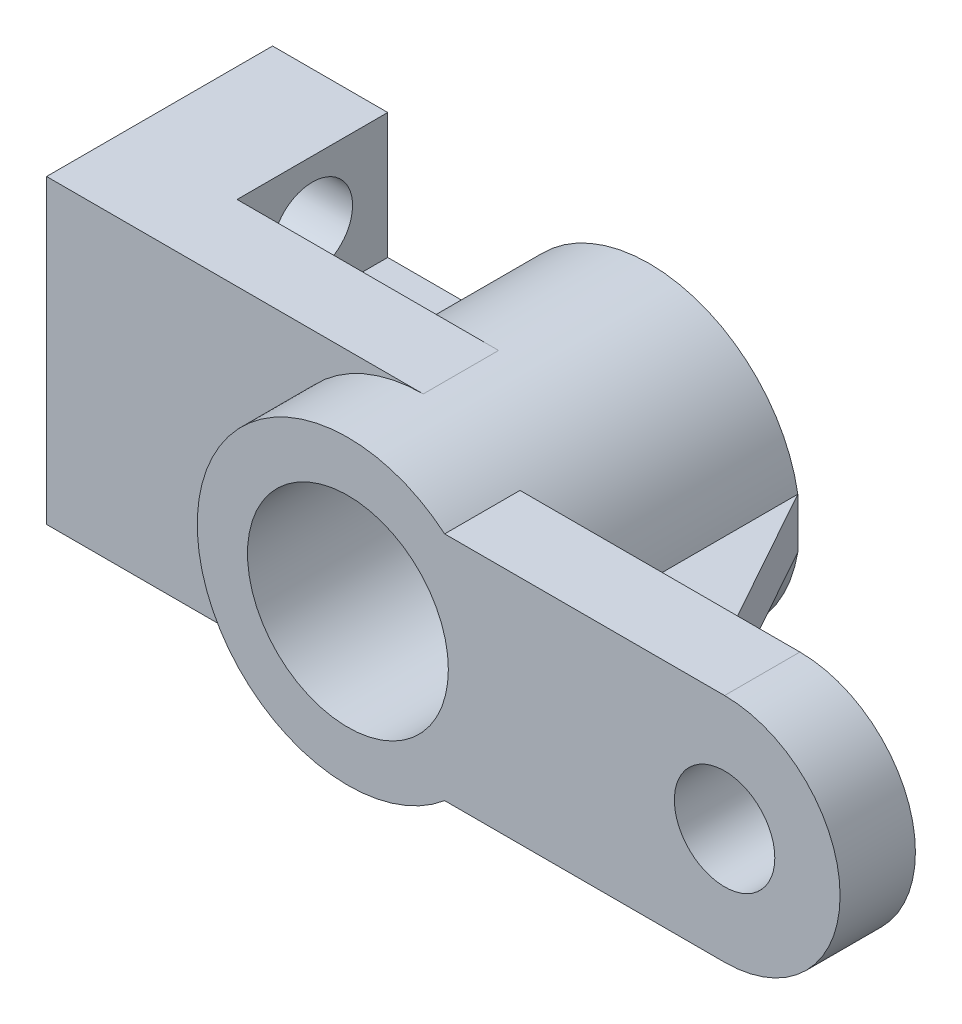
SolidWorks part; units mm, degrees
ref_plane "Front Plane" through (0, 0, 0) normal (0, 0, 1) x (1, 0, 0)
ref_plane "Top Plane" through (0, 0, 0) normal (0, 1, 0) x (1, 0, 0)
ref_plane "Right Plane" through (0, 0, 0) normal (1, 0, 0) x (0, 0, -1)
sketch "Sketch1" plane through (0, 0, 0) normal (0, 0, 1) x (1, 0, 0)
  circle A0 centre (0, 0) radius 30
  circle A1 centre (0, 0) radius 20
  dimension "D1" = 60
  dimension "D2" = 40
extrude "Boss-Extrude1" add sketch "Sketch1" along normal blind 60
sketch "Sketch2" plane through (0, 0, 60) normal (0, 0, 1) x (1, 0, 0)
  line L0 (19.2614, 23) -> (75, 23)
  line L1 (75, -23) -> (19.2614, -23)
  line L2 (0, 0) -> (75, 0) construction
  circle A0 centre (0, 0) radius 30 construction
  arc A1 (75, 23) -> (75, -23) centre (75, 0) cw
  circle A2 centre (75, 0) radius 10
  dimension "D1" = 23
  dimension "D2" = 20
  dimension "D3" = 75
extrude "Boss-Extrude3" add sketch "Sketch2" against normal blind 15
sketch "Sketch3" plane through (0, 0, 60) normal (0, 0, 1) x (1, 0, 0)
  line L0 (0, -30) -> (-75, -30)
  line L1 (0, 30) -> (-75, 30)
  line L2 (-75, 30) -> (-75, -30)
  arc A0 (19.2614, 23) -> (19.2614, -23) centre (0, 0) ccw construction
  arc A1 (0, 30) -> (0, -30) centre (0, 0) ccw
  dimension "D1" = 75
  dimension "D2" = 60
extrude "Boss-Extrude4" add sketch "Sketch3" against normal blind 15 from offset 15 offset against normal yes
sketch "Sketch5" plane through (0, 0, 0) normal (0, 0, -1) x (-1, 0, 0)
  line L0 (30, 0) -> (75, 0) construction
  line L2 (75, 30) -> (52.0709, 30)
  line L3 (0, 30) -> (75, 30) construction
  line L4 (52.0709, 30) -> (52.0709, 5)
  line L5 (75, -30) -> (0, -30) construction
  line L6 (52.0709, -30) -> (75, -30)
  line L7 (75, -5) -> (75, -4.9263)
  line L8 (52.0709, 5) -> (29.5804, 5)
  line L9 (75.2145, -5) -> (75, -5)
  line L11 (75.2145, 5) -> (75, 5)
  line L13 (75.2145, -5) -> (75, -4.9263) construction
  line L14 (75.2145, 5) -> (75, 4.981) construction
  line L17 (52.0709, -5) -> (29.5804, -5)
  line L18 (75, 4.981) -> (75, 5)
  line L19 (75, -30) -> (75, 30)
  line L20 (52.0709, -5) -> (52.0709, -30)
  arc A1 (0, -30) -> (0, 30) centre (0, 0) ccw construction
  arc A2 (29.5804, -5) -> (29.5804, 5) centre (0, 0) ccw
  point P11 (52.0709, 2.9503)
  circle M6 centre (0, 0) radius 30
  dimension "D1" = 5
extrude "Boss-Extrude8" add sketch "Sketch5" against normal up to surface (30 mm away) contours L17 L20 L6 L19 L7 L18 L2 L4 L8 M6 up to face at (-45, 0, 30)
sketch "Sketch9" plane through (-75, 0, 0) normal (-1, 0, 0) x (0, 0, 1)
  line L0 (0, 0) -> (45, 0) construction
  line L1 (45, -30) -> (45, 30) construction
  line L2 (0, -30) -> (0, 30) construction
  circle A0 centre (15, -17.5) radius 8
  circle A1 centre (15, 17.5) radius 8
  dimension "D1" = 15
  dimension "D2" = 16
  dimension "D3" = 35
extrude "Cut-Extrude2" cut sketch "Sketch9" against normal up to surface (22.9291 mm away) up to face at (-52.0709, 17.5, 15)
sketch "Sketch10" plane through (0, 0, 45) normal (0, 0, -1) x (-1, 0, 0)
  line L0 (0, 0) -> (-1.1528, 0) construction
  line L1 (-30, 0) -> (-98, 0) construction
  line L4 (-29.5804, 5) -> (-54.5804, 5)
  line L5 (-54.5804, -5) -> (-54.5804, 5)
  line L6 (-30, 0) -> (-54.5804, 5) construction
  line L7 (-29.5804, -5) -> (-54.5804, -5)
  line L8 (-54.5804, 0) -> (-30, 0)
  arc A0 (-75, 23) -> (-75, -23) centre (-75, 0) ccw construction
  arc A1 (-19.2614, 23) -> (-19.2614, -23) centre (0, 0) ccw construction
  arc A2 (-29.5804, 5) -> (-29.5804, -5) centre (0, 0) ccw
  point P6 (-30, 0)
  dimension "D1" = 25
  dimension "D2" = 5
extrude "Boss-Extrude9" add sketch "Sketch10" along normal up to vertex (45 mm away) contours L4 L5 L7 A2
sketch "Sketch11" plane through (0, 5, 0) normal (0, 1, 0) x (1, 0, 0)
  line L0 (29.5804, 0) -> (54.5804, -45)
  line L1 (29.5804, 0) -> (54.5804, 0)
  line L2 (54.5804, 0) -> (54.5804, -45)
extrude "Cut-Extrude8" cut sketch "Sketch11" against normal up to surface (10 mm away) up to face at (42.0804, -5, 22.5)
